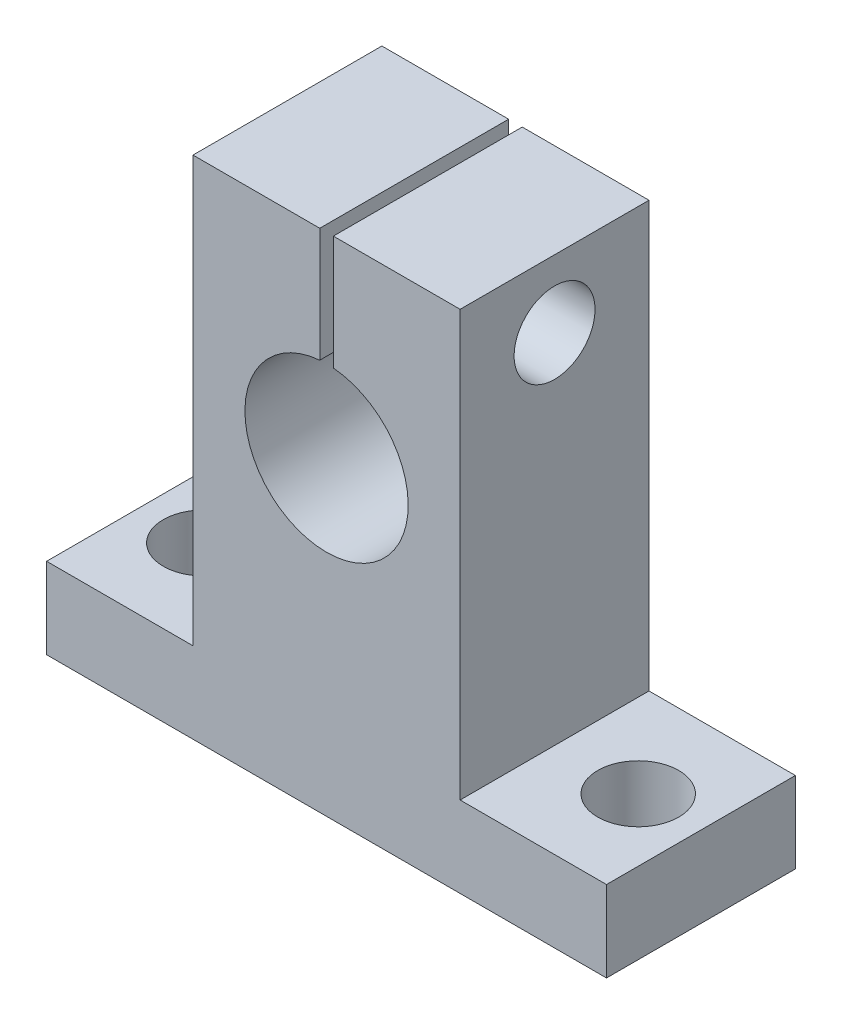
SolidWorks part; units mm, degrees
ref_plane "Ön Düzlem" through (0, 0, 0) normal (0, 0, 1) x (1, 0, 0)
ref_plane "Üst Düzlem" through (0, 0, 0) normal (0, 1, 0) x (1, 0, 0)
ref_plane "Sağ Düzlem" through (0, 0, 0) normal (1, 0, 0) x (0, 0, -1)
sketch "Çizim2" plane through (0, 0, 0) normal (0, 0, 1) x (1, 0, 0)
  line L0 (-0.5042, 14.5) -> (-9.9, 14.5)
  line L1 (9.9, 14.5) -> (0.5042, 14.5)
  line L2 (9.9, 14.5) -> (9.9, -17)
  line L4 (-9.9, 14.5) -> (-9.9, -17)
  line L6 (0.5042, 14.5) -> (0.5042, 6.029)
  line L7 (-9.9, -17) -> (-20.75, -17)
  line L8 (20.75, -23) -> (-20.75, -23)
  line L9 (20.75, -23) -> (20.75, -17)
  line L10 (20.75, -17) -> (9.9, -17)
  line L11 (-20.75, -23) -> (-20.75, -17)
  line L13 (-0.5042, 14.5) -> (-0.5042, 6.029)
  line L14 (0, 0) -> (0, 18.8177) construction
  arc A1 (-0.5042, 6.029) -> (0.5042, 6.029) centre (0, 0) ccw
  point P0 (0, 0)
  dimension "D2" = 23
  dimension "D8" = 12.1
  dimension "D1" = 19.8
  dimension "D3" = 41.5
  dimension "D4" = 31.5
  dimension "D5" = 6
  dimension "D9" = 1.0083
extrude "Yükseklik-Ekstrüzyon2" add sketch "Çizim2" against normal blind 14 contours L4 L7 L11 L8 L9 L10 L2 L1 L6 A1 L13 L0
sketch "Çizim3" plane through (-9.9, 0, 0) normal (-1, 0, 0) x (0, 0, 1)
  line L0 (0, 14.5) -> (0, -17) construction
  line L1 (-14, 14.5) -> (0, 14.5) construction
  circle A1 centre (-7, 9.5) radius 3
  dimension "D1" = 6
  dimension "D3" = 7
  dimension "D4" = 5
extrude "Kes-Ekstrüzyon1" cut sketch "Çizim3" against normal blind 30
sketch "Çizim4" plane through (0, -17, 0) normal (0, 1, 0) x (1, 0, 0)
  line L0 (-9.9, 0) -> (-20.75, 0) construction
  line L2 (0, -6.6227) -> (0, 42.2422) construction
  circle A1 centre (-16.1, 7) radius 3
  circle A2 centre (16.1, 7) radius 3
  dimension "D1" = 6
  dimension "D2" = 32.2
  dimension "D3" = 7
extrude "Kes-Ekstrüzyon2" cut sketch "Çizim4" against normal through all
